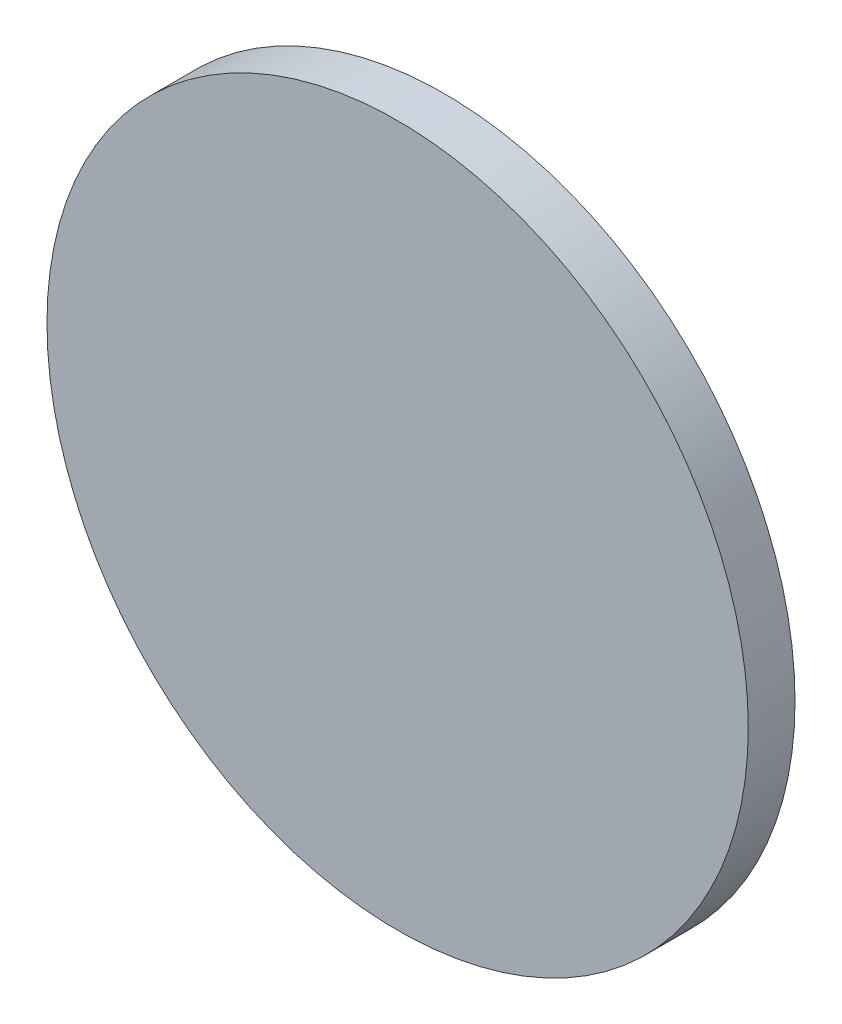
SolidWorks part; units mm, degrees
ref_plane "Спереди" through (0, 0, 0) normal (0, 0, 1) x (1, 0, 0)
ref_plane "Сверху" through (0, 0, 0) normal (0, 1, 0) x (1, 0, 0)
ref_plane "Справа" through (0, 0, 0) normal (1, 0, 0) x (0, 0, -1)
sketch "Эскиз1" plane through (0, 0, 0) normal (0, 0, 1) x (1, 0, 0)
  circle A0 centre (0, 0) radius 15
  dimension "D1" = 30
extrude "Вытянуть1" add sketch "Эскиз1" along normal blind 2
